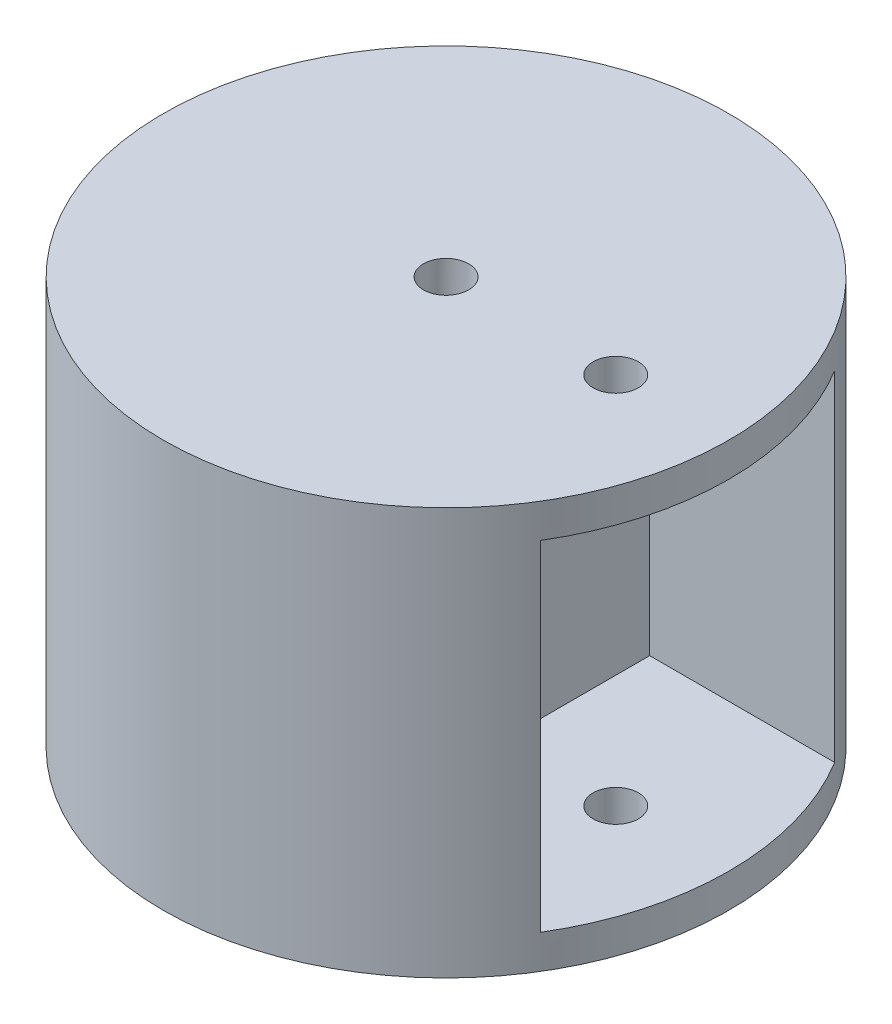
SolidWorks part; units mm, degrees
material "1060 Alloy"
ref_plane "Front Plane" through (0, 0, 0) normal (0, 0, 1) x (1, 0, 0)
ref_plane "Top Plane" through (0, 0, 0) normal (0, 1, 0) x (1, 0, 0)
ref_plane "Right Plane" through (0, 0, 0) normal (1, 0, 0) x (0, 0, -1)
sketch "Sketch1" plane through (0, 0, 0) normal (0, 1, 0) x (1, 0, 0)
  circle A0 centre (0, 0) radius 12.5
  dimension "D1" = 25
extrude "Boss-Extrude1" add sketch "Sketch1" along normal blind 18
sketch "Sketch2" plane through (0, 0, 0) normal (1, 0, 0) x (0, 0, -1)
  line L0 (-12.5, 18) -> (-12.5, 0) construction
  line L1 (-6.5, 16.5) -> (6.5, 16.5)
  line L2 (-6.5, 16.5) -> (-6.5, 1.5)
  line L3 (-6.5, 1.5) -> (6.5, 1.5)
  line L4 (6.5, 16.5) -> (6.5, 1.5)
  line L5 (-6.5, 16.5) -> (6.5, 1.5) construction
  line L6 (-6.5, 1.5) -> (6.5, 16.5) construction
  point P0 (0, 9)
  dimension "D1" = 15
  dimension "D2" = 13
  dimension "D3" = 9
  dimension "D4" = 12.5
extrude "Cut-Extrude1" [suppressed] cut sketch "Sketch2" along normal blind 18
sketch "Sketch3" plane through (0, 0, 0) normal (0, -1, 0) x (1, 0, 0)
  circle A1 centre (7.5, 0) radius 1
  dimension "D3" = 2
  dimension "D1" = 7.5
extrude "Cut-Extrude2" cut sketch "Sketch3" against normal through all
sketch "Sketch5" plane through (0, 0, 0) normal (0, -1, 0) x (1, 0, 0)
  line L1 (-1.4142, 0.5) -> (-2.5142, 0.5)
  line L3 (-1.4142, -0.5) -> (-2.5142, -0.5)
  line L4 (-2.5142, 0.5) -> (-2.5142, -0.5)
  arc A0 (-1.4142, -0.5) -> (-1.4142, 0.5) centre (0, 0) ccw
  point P3 (-1.5, 0)
  dimension "D1" = 3
  dimension "D2" = 1.1
  dimension "D3" = 1
ref_plane "Plane1" through (12.5, 0, 0) normal (1, 0, 0) x (0, 0, -1)
sketch "Sketch6" plane through (12.5, 0, 0) normal (1, 0, 0) x (0, 0, -1)
  line L0 (0, 0) -> (0, 18) construction
  line L1 (-6.5, 16.5) -> (6.5, 16.5)
  line L2 (-6.5, 16.5) -> (-6.5, 1.5)
  line L3 (-6.5, 1.5) -> (6.5, 1.5)
  line L4 (6.5, 16.5) -> (6.5, 1.5)
  line L5 (-6.5, 16.5) -> (6.5, 1.5) construction
  line L6 (-6.5, 1.5) -> (6.5, 16.5) construction
  line L7 (12.5, 18) -> (-12.5, 18) construction
  point P0 (0, 9)
  dimension "D1" = 15
  dimension "D2" = 13
extrude "Cut-Extrude3" cut sketch "Sketch6" against normal blind 10
extrude "Cut-Extrude4" cut sketch "Sketch5" against normal blind 16
sketch "Sketch7" plane through (0, 18, 0) normal (0, 1, 0) x (1, 0, 0)
  circle A0 centre (0, 0) radius 1
  dimension "D1" = 2
extrude "Cut-Extrude5" cut sketch "Sketch7" against normal blind 16
